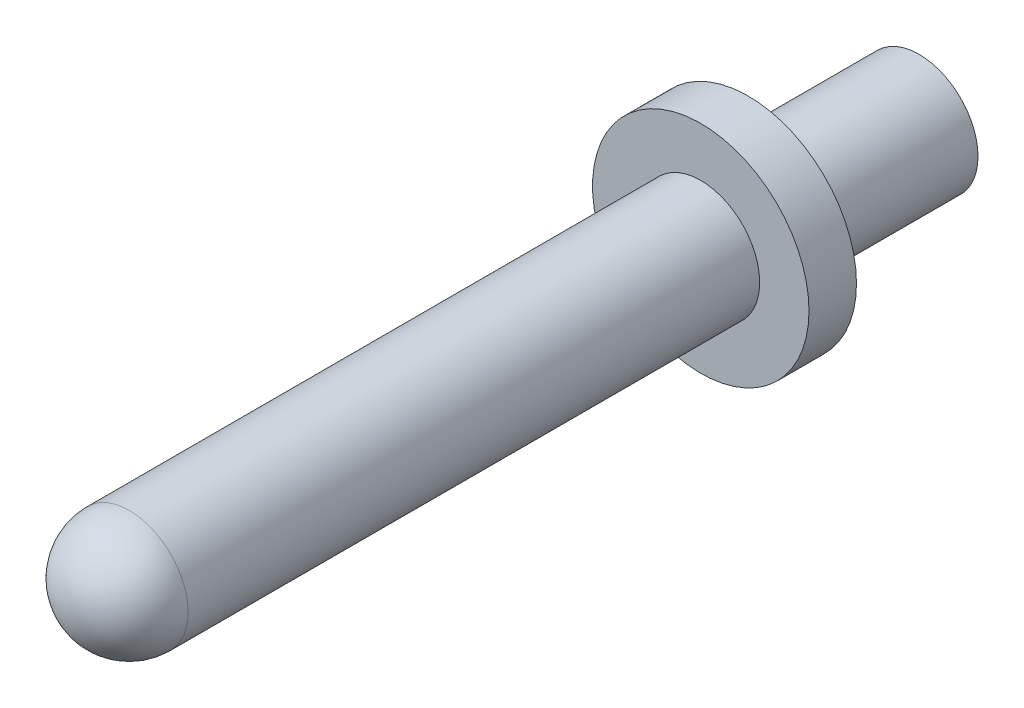
SolidWorks part; units mm, degrees
ref_plane "Front Plane" through (0, 0, 0) normal (0, 0, 1) x (1, 0, 0)
ref_plane "Top Plane" through (0, 0, 0) normal (0, 1, 0) x (1, 0, 0)
ref_plane "Right Plane" through (0, 0, 0) normal (1, 0, 0) x (0, 0, -1)
sketch "Sketch1" plane through (0, 0, 0) normal (0, 1, 0) x (1, 0, 0)
  line L0 (0.5461, 9.0678) -> (0, 8.7503)
  line L1 (0, 0) -> (0.7874, 0)
  line L2 (0, 0) -> (0, 8.4328)
  line L3 (0, 8.4328) -> (0.7874, 8.4328)
  line L4 (0.7874, 0) -> (0.7874, 8.4328)
  line L5 (0, 8.4328) -> (1.4478, 8.4328)
  line L6 (0, 8.4328) -> (0, 9.0678)
  line L7 (0, 9.0678) -> (1.4478, 9.0678)
  line L8 (1.4478, 8.4328) -> (1.4478, 9.0678)
  line L9 (0.5461, 9.0678) -> (0.7874, 9.0678)
  line L10 (0.5461, 9.0678) -> (0.5461, 11.3538)
  line L11 (0.5461, 11.3538) -> (0.7874, 11.3538)
  line L12 (0.7874, 9.0678) -> (0.7874, 11.3538)
  circle A0 centre (0, 0.7874) radius 0.7874
  dimension "D1" = 8.4328
  dimension "D2" = 0.7874
  dimension "D3" = 0.635
  dimension "D4" = 0.5461
  dimension "D5" = 0.7874
  dimension "D6" = 2.286
  dimension "D7" = 1.4478
  dimension "D8" = 0.3175
revolve "Revolve1" add sketch "Sketch1" angle 360 about L2
